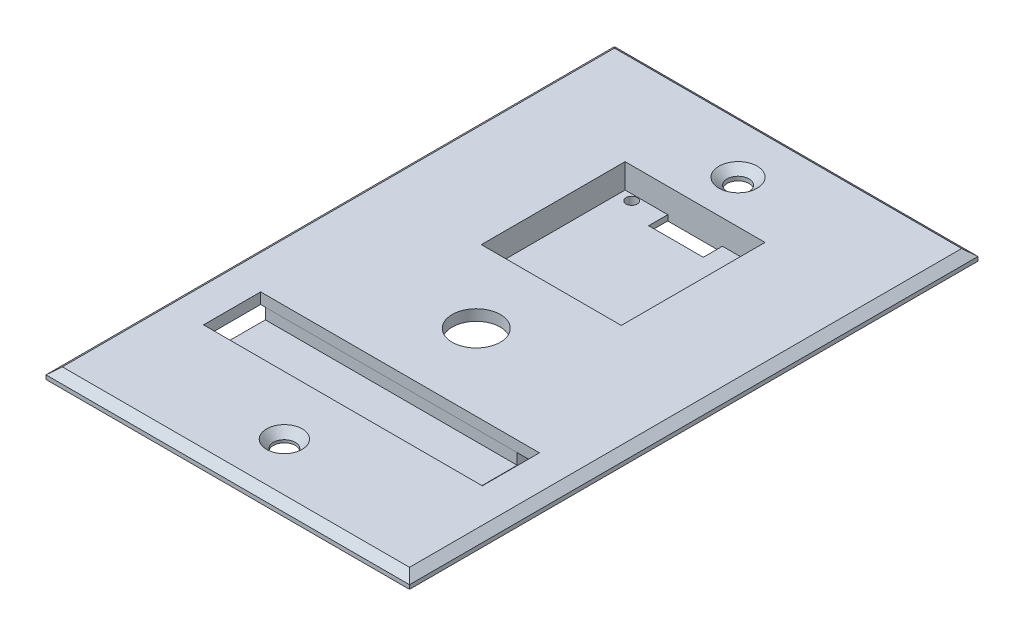
SolidWorks part; units mm, degrees
ref_plane "Front Plane" through (0, 0, 0) normal (0, 0, 1) x (1, 0, 0)
ref_plane "Top Plane" through (0, 0, 0) normal (0, 1, 0) x (1, 0, 0)
ref_plane "Right Plane" through (0, 0, 0) normal (1, 0, 0) x (0, 0, -1)
sketch "Sketch1" plane through (0, 0, 0) normal (0, 1, 0) x (1, 0, 0)
  line L5 (-25.75, 44.5) -> (25.75, -44.5) construction
  line L6 (-25.75, -44.5) -> (25.75, 44.5) construction
  line L10 (-33.25, 52.1437) -> (-33.25, -51.8563)
  line L11 (-33.25, -51.8563) -> (33.25, -51.8563)
  line L12 (33.25, 52.1437) -> (33.25, -51.8563)
  line L13 (-33.25, 52.1437) -> (33.25, 52.1437)
  line L14 (-25.75, 0) -> (25.75, 0) construction
  circle A0 centre (0, 41.4977) radius 2
  circle A1 centre (0, -41.4977) radius 2
  point P0 (0, 0)
extrude "Boss-Extrude2" add sketch "Sketch1" along normal blind 2 contours L10 L11 L12 L13
sketch "Sketch2" plane through (0, 0, 0) normal (0, 1, 0) x (1, 0, 0)
  line L1 (-25.75, 44.5) -> (25.75, 44.5)
  line L2 (-25.75, 44.5) -> (-25.75, -44.5)
  line L3 (-25.75, -44.5) -> (25.75, -44.5)
  line L4 (25.75, 44.5) -> (25.75, -44.5)
  line L5 (-25.75, 44.5) -> (25.75, -44.5) construction
  line L6 (-25.75, -44.5) -> (25.75, 44.5) construction
  circle A0 centre (0, 41.5) radius 2
  circle A1 centre (0, -41.5) radius 2
  point P0 (0, 0)
extrude "Cut-Extrude8" cut sketch "Sketch2" along normal blind 2 contours A1 | A0
chamfer "Chamfer1" distance 1.5 angle 40 6 edges at (0, 2, 39.5) (0, 2, -39.5) (33.25, 2, -0.1437) (0, 2, 51.8563) (-33.25, 2, -0.1437) (0, 2, -52.1437)
sketch "Sketch4" plane through (0, 2, 0) normal (0, 1, 0) x (1, 0, 0)
  line L0 (0, 38) -> (25.75, 38) construction
  line L1 (-25.75, 44.5) -> (25.75, 44.5)
  line L2 (-25.75, 44.5) -> (-25.75, -44.5)
  line L3 (-25.75, -44.5) -> (25.75, -44.5)
  line L4 (25.75, 44.5) -> (25.75, -44.5)
  line L5 (-25.75, 44.5) -> (25.75, -44.5) construction
  line L6 (-25.75, -44.5) -> (25.75, 44.5) construction
  line L7 (-25.75, 0) -> (25.75, 0) construction
  line L8 (0, -38) -> (25.75, -38) construction
  line L10 (-12.7, 34.3955) -> (12.7, 34.3955)
  line L11 (-12.7, 34.3955) -> (-12.7, 8.2955)
  line L12 (-12.7, 8.2955) -> (12.7, 8.2955)
  line L13 (12.7, 34.3955) -> (12.7, 8.2955)
  line L14 (-12.7, 34.3955) -> (12.7, 8.2955) construction
  line L15 (-12.7, 8.2955) -> (12.7, 34.3955) construction
  line L16 (-25.5, -20.6952) -> (25.5, -20.6952)
  line L17 (-25.5, -20.6952) -> (-25.5, -31.1952)
  line L18 (-25.5, -31.1952) -> (25.5, -31.1952)
  line L19 (25.5, -20.6952) -> (25.5, -31.1952)
  line L20 (-25.5, -20.6952) -> (25.5, -31.1952) construction
  line L21 (-25.5, -31.1952) -> (25.5, -20.6952) construction
  circle A0 centre (0, 41.5) radius 3.5 construction
  circle A1 centre (0, -6.3965) radius 4.4
  point P1 (0, 0)
  point P14 (0, 21.3455)
  point P21 (0, -25.9452)
  dimension "D6" = 51
  dimension "D1" = 89
  dimension "D2" = 51.5
  dimension "D3" = 76
  dimension "D4" = 26.1
  dimension "D5" = 25.4
  dimension "D7" = 10.5
extrude "Cut-Extrude9" cut sketch "Sketch4" against normal blind 5.5 contours A1
sketch "Sketch5" plane through (0, 2, 0) normal (0, 1, 0) x (1, 0, 0)
  line L1 (-12.8, 33.6331) -> (12.8, 33.6331)
  line L2 (-12.8, 33.6331) -> (-12.8, 7.3331)
  line L3 (-12.8, 7.3331) -> (12.8, 7.3331)
  line L4 (12.8, 33.6331) -> (12.8, 7.3331)
  line L5 (-12.8, 33.6331) -> (12.8, 7.3331) construction
  line L6 (-12.8, 7.3331) -> (12.8, 33.6331) construction
  point P0 (0, 20.4831)
  dimension "D1" = 26.3
  dimension "D2" = 25.6
extrude "Cut-Extrude13" cut sketch "Sketch5" against normal blind 3.5
sketch "Sketch10" plane through (0, 0, 0) normal (0, -1, 0) x (1, 0, 0)
  line L1 (14.6616, -36.007) -> (-14.6616, -36.007)
  line L2 (14.6616, -36.007) -> (14.6616, -5.1028)
  line L3 (14.6616, -5.1028) -> (-14.6616, -5.1028)
  line L4 (-14.6616, -36.007) -> (-14.6616, -5.1028)
extrude "Boss-Extrude8" add sketch "Sketch10" along normal blind 3.5
sketch "Sketch11" plane through (0, 0, 0) normal (0, 1, 0) x (1, 0, 0)
  line L1 (-12.8, 33.6331) -> (12.8, 33.6331)
  line L2 (-12.8, 33.6331) -> (-12.8, 7.3331)
  line L3 (-12.8, 7.3331) -> (12.8, 7.3331)
  line L4 (12.8, 33.6331) -> (12.8, 7.3331)
extrude "Cut-Extrude14" cut sketch "Sketch11" against normal blind 2.5
ref_plane "Plane1" through (-12.8, -2.5, -33.6331) normal (-1, 0, 0) x (0, 0, 1)
sketch "Sketch13" plane through (0, -2.5, 0) normal (0, 1, 0) x (1, 0, 0)
  line L0 (0, 33.6331) -> (0, 19.7557) construction
  line L1 (12.8, 33.6331) -> (-12.8, 33.6331) construction
  circle A0 centre (-10.4902, 32.5266) radius 1.0244
  circle A1 centre (10.4902, 32.5266) radius 1.0244
  point P9 (-10.4902, 32.5266)
extrude "Cut-Extrude17" cut sketch "Sketch13" against normal blind 2.5
sketch "Sketch16" plane through (0, -2.5, 0) normal (0, 1, 0) x (1, 0, 0)
  circle A0 centre (-10.4754, 9.6899) radius 1
  circle A1 centre (10.505, 9.6899) radius 1
extrude "Cut-Extrude18" cut sketch "Sketch16" against normal blind 2.5
sketch "Sketch18" plane through (0, -3.5, 0) normal (0, -1, 0) x (1, 0, 0)
  line L1 (-14.6616, -5.1028) -> (-8.6893, -5.1028)
  line L2 (-14.6616, -5.1028) -> (-14.6616, -11.1442)
  line L3 (-14.6616, -11.1442) -> (-8.6893, -11.1442)
  line L4 (-8.6893, -5.1028) -> (-8.6893, -11.1442)
extrude "Boss-Extrude9" add sketch "Sketch18" along normal blind 2.5
sketch "Sketch19" plane through (0, -3.5, 0) normal (0, -1, 0) x (-1, 0, 0)
  line L1 (-14.6616, 5.1028) -> (-8.7682, 5.1028)
  line L2 (-14.6616, 5.1028) -> (-14.6616, 11.1399)
  line L3 (-14.6616, 11.1399) -> (-8.7682, 11.1399)
  line L4 (-8.7682, 5.1028) -> (-8.7682, 11.1399)
extrude "Boss-Extrude10" add sketch "Sketch19" along normal blind 2.5
sketch "Sketch20" plane through (0, -3.5, 0) normal (0, -1, 0) x (-1, 0, 0)
  line L1 (14.6616, 36.007) -> (8.6244, 36.007)
  line L2 (14.6616, 36.007) -> (14.6616, 29.9699)
  line L3 (14.6616, 29.9699) -> (8.6244, 29.9699)
  line L4 (8.6244, 36.007) -> (8.6244, 29.9699)
extrude "Screen screw hole" add sketch "Sketch20" along normal blind 2.5
sketch "Sketch21" plane through (0, -3.5, 0) normal (0, -1, 0) x (-1, 0, 0)
  line L1 (-14.6616, 36.007) -> (-8.6244, 36.007)
  line L2 (-14.6616, 36.007) -> (-14.6616, 29.9699)
  line L3 (-14.6616, 29.9699) -> (-8.6244, 29.9699)
  line L4 (-8.6244, 36.007) -> (-8.6244, 29.9699)
extrude "Boss-Extrude12" add sketch "Sketch21" along normal blind 2.5
sketch "Sketch22" plane through (0, -2.5, 0) normal (0, 1, 0) x (1, 0, 0)
  circle A0 centre (-10.4902, 32.5266) radius 1.0244
extrude "Cut-Extrude20" cut sketch "Sketch22" against normal blind 3.5
sketch "Sketch24" plane through (0, -2.5, 0) normal (0, 1, 0) x (1, 0, 0)
  line L0 (0, 33.6331) -> (0, 7.3331) construction
  line L1 (12.8, 33.6331) -> (-12.8, 33.6331) construction
  line L2 (-12.8, 7.3331) -> (12.8, 7.3331) construction
  line L3 (0, 29.3596) -> (-5, 29.3596)
  line L4 (-4.9944, 33.6331) -> (5.0056, 33.6331)
  line L5 (-4.9944, 33.6331) -> (-4.9944, 30.1331)
  line L6 (-4.9944, 30.1331) -> (5.0056, 30.1331)
  line L7 (5.0056, 33.6331) -> (5.0056, 30.1331)
  line L8 (-5, 29.3596) -> (-5, 33.6331)
  dimension "D1" = 3.5
  dimension "D2" = 10
extrude "Cut-Extrude21" cut sketch "Sketch24" against normal blind 3.5 contours L5 L4 L7 L6
sketch "Sketch26" plane through (0, 2, 0) normal (0, 1, 0) x (1, 0, 0)
  line L0 (0, 50.6437) -> (0, -50.3563) construction
  line L1 (-25.5, -20.3393) -> (25.5, -20.3393)
  line L2 (-25.5, -20.3393) -> (-25.5, -30.7893)
  line L3 (-25.5, -30.7893) -> (25.5, -30.7893)
  line L4 (25.5, -20.3393) -> (25.5, -30.7893)
  line L5 (31.75, 50.6437) -> (-31.75, 50.6437) construction
  line L6 (-31.75, -50.3563) -> (31.75, -50.3563) construction
extrude "Cut-Extrude22" cut sketch "Sketch26" against normal blind 3.5
sketch "Sketch27" plane through (0, 0, 0) normal (0, -1, 0) x (-1, 0, 0)
  line L5 (-25.5, -17.5792) -> (25.639, -17.5792)
  line L6 (-25.5, -17.5792) -> (-25.5, -33.3966)
  line L7 (-25.5, -33.3966) -> (25.639, -33.3966)
  line L8 (25.639, -17.5792) -> (25.639, -33.3966)
extrude "Boss-Extrude18" add sketch "Sketch27" along normal blind 3 separate body
sketch "Sketch29" plane through (0, 0, 0) normal (0, 1, 0) x (1, 0, 0)
  line L1 (-25.5, -20.3393) -> (25.5, -20.3393)
  line L2 (-25.5, -20.3393) -> (-25.5, -30.7893)
  line L3 (-25.5, -30.7893) -> (25.5, -30.7893)
  line L4 (25.5, -20.3393) -> (25.5, -30.7893)
extrude "Cut-Extrude24" cut sketch "Sketch29" against normal blind 2
sketch "Sketch30" plane through (0, -3, 0) normal (0, -1, 0) x (-1, 0, 0)
  line L0 (25.639, -17.5792) -> (-25.5, -17.5792) construction
  line L1 (-25.5, -33.3966) -> (-21.4351, -33.3966)
  line L2 (-25.5, -33.3966) -> (-25.5, -17.5792)
  line L3 (-25.5, -17.5792) -> (-21.4351, -17.5792)
  line L4 (-21.4351, -33.3966) -> (-21.4351, -17.5792)
extrude "Cut-Extrude25" cut sketch "Sketch30" against normal blind 3
sketch "Sketch31" plane through (0, 0, 0) normal (0, -1, 0) x (-1, 0, 0)
  line L1 (-25.5, -30.7893) -> (-28.4879, -30.7893)
  line L2 (-25.5, -30.7893) -> (-25.5, -20.3393)
  line L3 (-25.5, -20.3393) -> (-28.4879, -20.3393)
  line L4 (-28.4879, -30.7893) -> (-28.4879, -20.3393)
extrude "Cut-Extrude26" cut sketch "Sketch31" against normal blind 0.75
sketch "Sketch32" plane through (-25.639, 0, 0) normal (-1, 0, 0) x (0, 0, 1)
  line L1 (17.5792, 0) -> (33.3966, 0)
  line L2 (17.5792, 0) -> (17.5792, -3)
  line L3 (17.5792, -3) -> (33.3966, -3)
  line L4 (33.3966, 0) -> (33.3966, -3)
extrude "Cut-Extrude27" cut sketch "Sketch32" against normal blind 1
